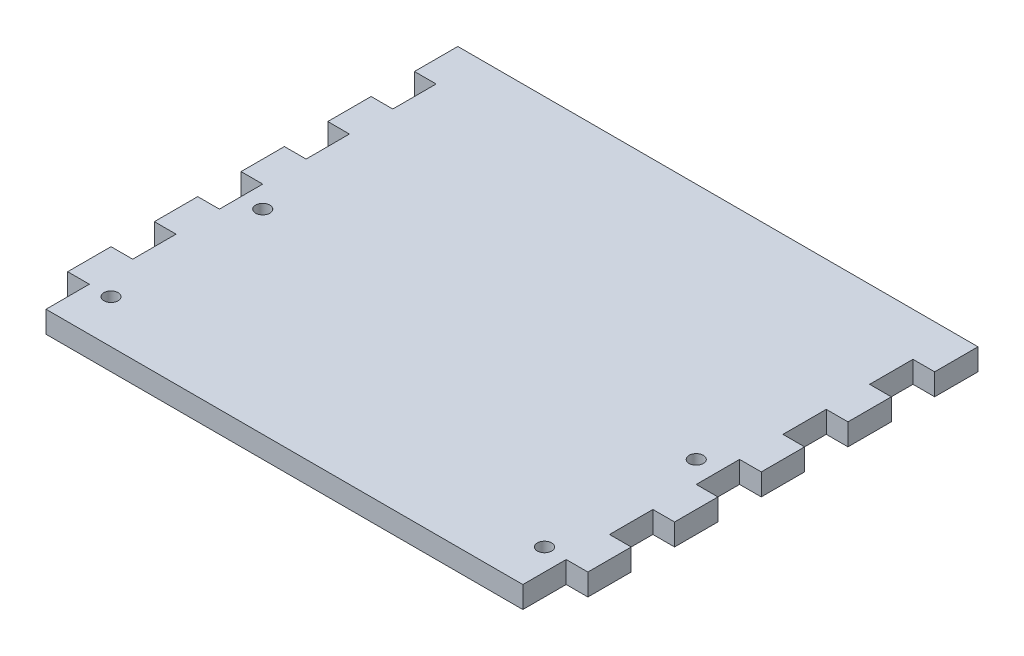
SolidWorks part; units mm, degrees
ref_plane "Front Plane" through (0, 0, 0) normal (0, 0, 1) x (1, 0, 0)
ref_plane "Top Plane" through (0, 0, 0) normal (0, 1, 0) x (1, 0, 0)
ref_plane "Right Plane" through (0, 0, 0) normal (1, 0, 0) x (0, 0, -1)
sketch "Sketch2" plane through (0, 0, 0) normal (0, 1, 0) x (1, 0, 0)
  line L0 (3.175, 0) -> (3.175, 12.7)
  line L1 (3.175, 12.7) -> (-3.175, 12.7)
  line L2 (-3.175, 12.7) -> (-3.175, 25.4)
  line L3 (-3.175, 25.4) -> (3.175, 25.4)
  line L4 (3.175, 38.1) -> (-3.175, 38.1)
  line L5 (-3.175, 38.1) -> (-3.175, 50.8)
  line L6 (-3.175, 50.8) -> (3.175, 50.8)
  line L7 (3.175, 63.5) -> (-3.175, 63.5)
  line L8 (-3.175, 63.5) -> (-3.175, 76.2)
  line L9 (-3.175, 76.2) -> (3.175, 76.2)
  line L10 (3.175, 25.4) -> (3.175, 38.1)
  line L11 (3.175, 88.9) -> (-3.175, 88.9)
  line L12 (-3.175, 88.9) -> (-3.175, 101.6)
  line L13 (-3.175, 101.6) -> (3.175, 101.6)
  line L14 (3.175, 50.8) -> (3.175, 63.5)
  line L15 (3.175, 114.3) -> (-3.175, 114.3)
  line L16 (-3.175, 114.3) -> (-3.175, 127)
  line L17 (-3.175, 127) -> (3.175, 127)
  line L18 (3.175, 76.2) -> (3.175, 88.9)
  line L19 (9.525, 0) -> (9.525, 12.7) construction
  line L20 (136.525, 0) -> (136.525, 12.7) construction
  line L22 (3.175, 101.6) -> (3.175, 114.3)
  line L23 (73.025, 127) -> (73.025, 0) construction
  line L24 (142.875, 57.15) -> (136.525, 57.15) construction
  line L27 (142.875, 101.6) -> (142.875, 114.3)
  line L30 (142.875, 76.2) -> (142.875, 88.9)
  line L31 (149.225, 127) -> (142.875, 127)
  line L32 (149.225, 114.3) -> (149.225, 127)
  line L33 (142.875, 114.3) -> (149.225, 114.3)
  line L34 (142.875, 50.8) -> (142.875, 63.5)
  line L35 (149.225, 101.6) -> (142.875, 101.6)
  line L36 (149.225, 88.9) -> (149.225, 101.6)
  line L37 (142.875, 88.9) -> (149.225, 88.9)
  line L38 (142.875, 25.4) -> (142.875, 38.1)
  line L39 (149.225, 76.2) -> (142.875, 76.2)
  line L40 (149.225, 63.5) -> (149.225, 76.2)
  line L41 (142.875, 63.5) -> (149.225, 63.5)
  line L42 (149.225, 50.8) -> (142.875, 50.8)
  line L43 (149.225, 38.1) -> (149.225, 50.8)
  line L44 (142.875, 38.1) -> (149.225, 38.1)
  line L45 (149.225, 25.4) -> (142.875, 25.4)
  line L46 (149.225, 12.7) -> (149.225, 25.4)
  line L47 (142.875, 12.7) -> (149.225, 12.7)
  line L48 (142.875, 0) -> (142.875, 12.7)
  line L49 (142.875, 0) -> (3.175, 0)
  line L52 (3.175, 57.15) -> (9.525, 57.15) construction
  line L53 (3.175, 127) -> (142.875, 127)
  line L54 (-3.175, 152.4) -> (3.175, 152.4) [skipped]
  line L56 (3.175, 139.7) -> (-3.175, 139.7) [skipped]
  line L57 (-3.175, 139.7) -> (-3.175, 152.4) [skipped]
  circle A0 centre (136.525, 57.15) radius 2.0828
  circle A1 centre (9.525, 12.7) radius 2.0828
  circle A2 centre (9.525, 57.15) radius 2.0828
  circle A3 centre (136.525, 12.7) radius 2.0828
  dimension "D1" = 6
extrude "Boss-Extrude1" add sketch "Sketch2" along normal blind 6.35
